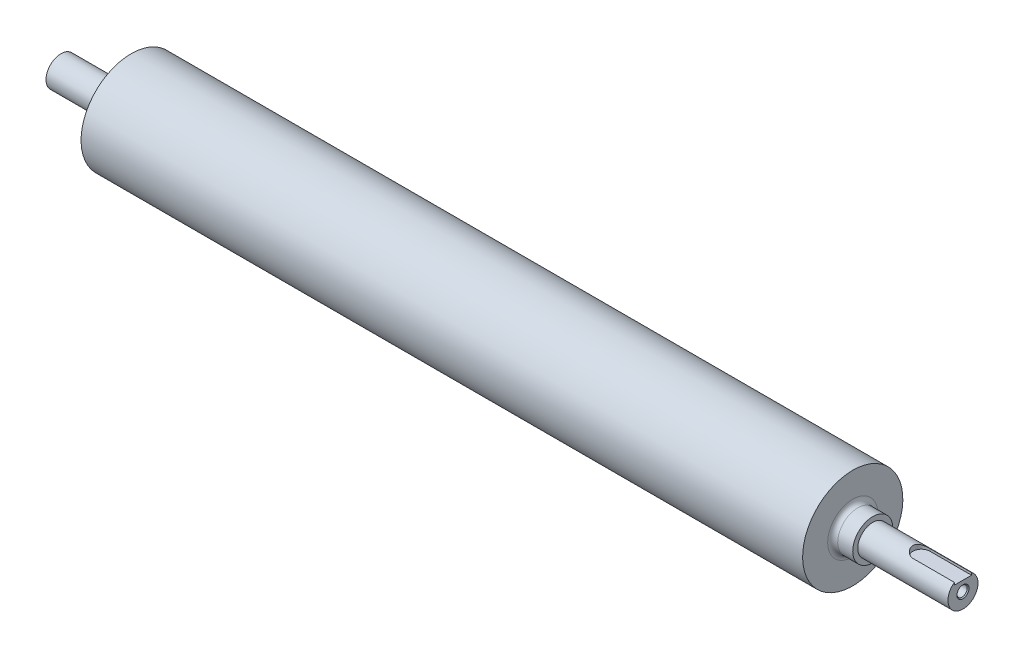
SolidWorks part; units mm, degrees
ref_plane "Front Plane" through (0, 0, 0) normal (0, 0, 1) x (1, 0, 0)
ref_plane "Top Plane" through (0, 0, 0) normal (0, 1, 0) x (1, 0, 0)
ref_plane "Right Plane" through (0, 0, 0) normal (1, 0, 0) x (0, 0, -1)
sketch "Sketch1" plane through (0, 0, 0) normal (0, 0, 1) x (1, 0, 0)
  line L0 (0, 0) -> (0, 15)
  line L1 (0, -55) -> (0, 55) construction
  line L2 (0, 15) -> (50, 15)
  line L3 (50, 15) -> (50, 20)
  line L4 (50, 20) -> (70, 20)
  line L5 (70, 20) -> (70, 50)
  line L6 (70, 50) -> (790, 50)
  line L7 (790, 50) -> (790, 20)
  line L8 (790, 20) -> (810, 20)
  line L9 (810, 20) -> (810, 15)
  line L10 (810, 15) -> (900, 15)
  line L11 (900, 15) -> (900, 0)
  line L12 (900, 0) -> (0, 0)
  dimension "D1" = 900
  dimension "D2" = 50
  dimension "D3" = 20
  dimension "D4" = 720
  dimension "D5" = 20
  dimension "D6" = 15
  dimension "D7" = 5
  dimension "D8" = 50
revolve "Revolve1" add sketch "Sketch1" angle 360 about L12
fillet "Fillet1" radius 5 2 edges at (70, 20, 0) (790, 20, 0)
hole_wizard "M12 Tapped Hole1" positions "3DSketch1" profile "Sketch2" tap size "M12" standard "ISO"
sketch3d "3DSketch1"
  line L0 (810, 0, 0) -> (900, 0, 0) construction
  circle A0 centre (0, 0, 0) radius 15 construction
  point P0 (900, 0, 0)
  point P4 (0, 0, 0)
  point P9 (15, 0, 0)
  dimension "D1" = 0
sketch "Sketch2" plane through (900, 0, 0) normal (0, 1, 0) x (0, 0, -1)
  line L0 (0, 0) -> (0, 32.3144)
  line L1 (0, 32.3144) -> (5.1, 29.25)
  line L2 (5.1, 29.25) -> (5.1, 0.925)
  line L3 (5.1, 0.925) -> (6.025, 0)
  line L5 (6.025, 0) -> (0, 0)
  line L6 (-5.1, 0.925) -> (-6.025, 0) construction
  line L10 (0, 32.3144) -> (-5.1, 29.25) construction
  line L11 (0, -6.35) -> (0, 107.95) construction
  dimension "Tap Drill Dia." = 10.2
  dimension "Tap Drill Depth" = 29.25
  dimension "Near C'Sink Dia." = 12.05
  dimension "Near C'Sink Angle" = 90
  dimension "Drill Angle" = 118
ref_plane "Plane1" through (0, 15, 0) normal (0, 1, 0) x (1, 0, 0)
sketch "Sketch3" plane through (0, 15, 0) normal (0, 1, 0) x (1, 0, 0)
  line L0 (858.5167, 0) -> (900, 0) construction
  line L1 (-55, 0) -> (55, 0) construction
  line L2 (900, -15) -> (900, 15) construction
  line L3 (858.5167, 8.5167) -> (900, 8.5167)
  line L4 (858.5167, -8.5167) -> (900, -8.5167)
  arc A0 (858.5167, 8.5167) -> (858.5167, -8.5167) centre (858.5167, 0) ccw
  arc A1 (900, -8.5167) -> (900, 8.5167) centre (900, 0) ccw
  point P6 (879.2583, 0)
  point P12 (850, 0)
  dimension "D1" = 17.0334
  dimension "D2" = 50
extrude "Cut-Extrude1" cut sketch "Sketch3" against normal blind 5
